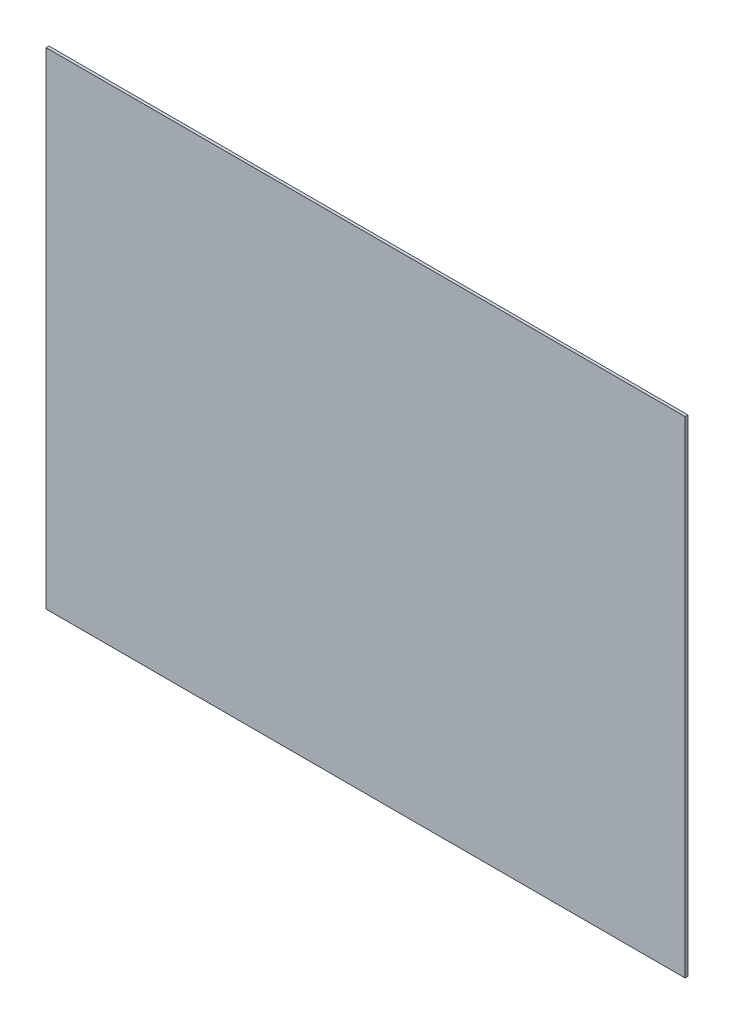
SolidWorks part; units mm, degrees
ref_plane "Front" through (0, 0, 0) normal (0, 0, 1) x (1, 0, 0)
ref_plane "Top" through (0, 0, 0) normal (0, 1, 0) x (1, 0, 0)
ref_plane "Right" through (0, 0, 0) normal (1, 0, 0) x (0, 0, -1)
sketch "Sketch1" plane through (0, 0, 0) normal (0, 0, 1) x (1, 0, 0)
  line L1 (-56.5, -43) -> (56.5, -43)
  line L2 (-56.5, -43) -> (-56.5, 43)
  line L3 (-56.5, 43) -> (56.5, 43)
  line L4 (56.5, -43) -> (56.5, 43)
  line L5 (-56.5, -43) -> (56.5, 43) construction
  line L6 (-56.5, 43) -> (56.5, -43) construction
  point P0 (0, 0)
  dimension "D1" = 86
  dimension "D2" = 113
extrude "Boss-Extrude1" add sketch "Sketch1" along normal blind 0.5
